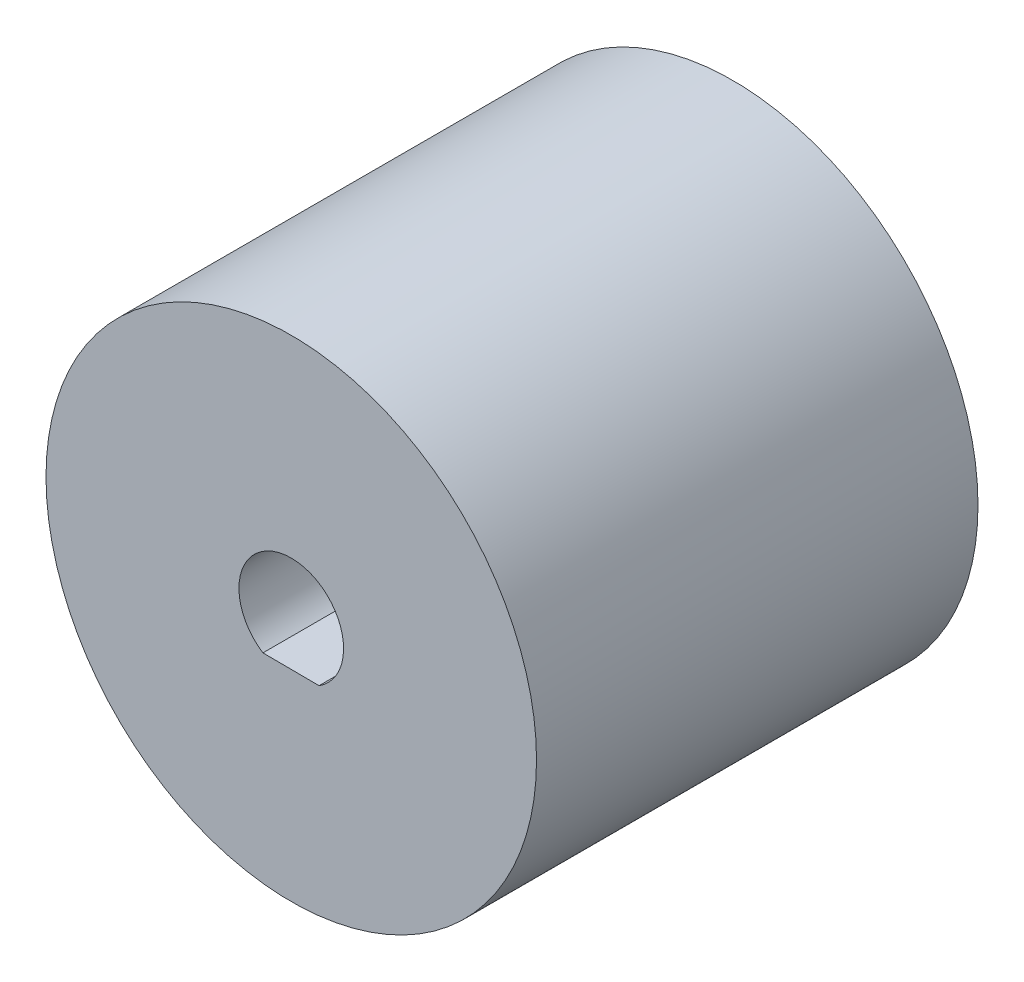
SolidWorks part; units mm, degrees
ref_plane "Front Plane" through (0, 0, 0) normal (0, 0, 1) x (1, 0, 0)
ref_plane "Top Plane" through (0, 0, 0) normal (0, 1, 0) x (1, 0, 0)
ref_plane "Right Plane" through (0, 0, 0) normal (1, 0, 0) x (0, 0, -1)
sketch "Sketch1" plane through (0, 0, 0) normal (0, 0, 1) x (1, 0, 0)
  line L5 (-1.7333, -2.6899) -> (1.7017, -2.71)
  circle A0 centre (0, 0) radius 15
  arc A7 (1.7017, -2.71) -> (-1.7333, -2.6899) centre (0, 0) ccw
  dimension "D1" = 30
extrude "Boss-Extrude1" add sketch "Sketch1" along normal blind 27
